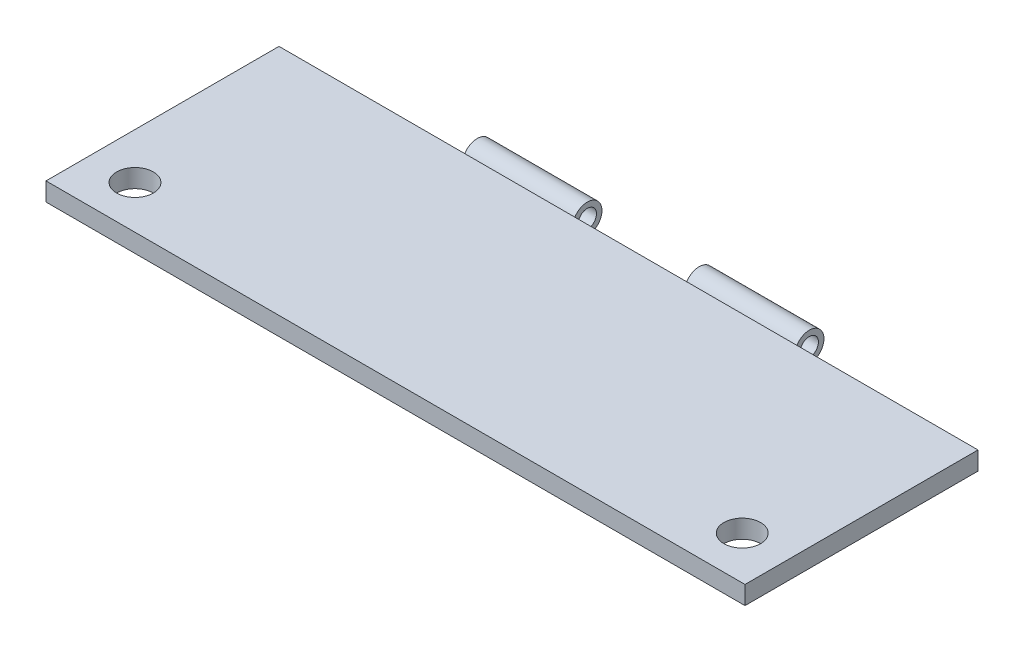
SolidWorks part; units mm, degrees
ref_plane "Alzado" through (0, 0, 0) normal (0, 0, 1) x (1, 0, 0)
ref_plane "Planta" through (0, 0, 0) normal (0, 1, 0) x (1, 0, 0)
ref_plane "Vista lateral" through (0, 0, 0) normal (1, 0, 0) x (0, 0, -1)
sketch "Croquis1" plane through (0, 0, 0) normal (0, 1, 0) x (1, 0, 0)
  line L1 (-38.1, -12.7) -> (38.1, -12.7)
  line L2 (-38.1, -12.7) -> (-38.1, 12.7)
  line L3 (-38.1, 12.7) -> (38.1, 12.7)
  line L4 (38.1, -12.7) -> (38.1, 12.7)
  line L5 (-38.1, -12.7) -> (38.1, 12.7) construction
  line L6 (-38.1, 12.7) -> (38.1, -12.7) construction
  point P0 (0, 0)
  dimension "D1" = 76.2
  dimension "D2" = 25.4
extrude "Saliente-Extruir1" add sketch "Croquis1" along normal blind 2
sketch "Croquis2" plane through (-38.1, 0, 0) normal (-1, 0, 0) x (0, 0, 1)
  circle A0 centre (-14.3062, 0.901) radius 1.6
extrude "Saliente-Extruir2" add sketch "Croquis2" against normal up to surface (76.2 mm away) separate body up to face at (38.1, 1, 0)
sketch "Croquis3" plane through (0, 2, 0) normal (0, 1, 0) x (1, 0, 0)
  line L0 (-38.1, 0) -> (-33.1, 0)
  line L1 (-38.1, 12.7) -> (-38.1, -12.7) construction
  line L2 (-33.1, 0) -> (-33.1, -8)
  line L3 (38.1, 0) -> (33.1, 0)
  line L4 (38.1, -12.7) -> (38.1, 12.7) construction
  line L5 (33.1, 0) -> (33.1, -8)
  circle A0 centre (-33.1, -8) radius 2
  circle A1 centre (33.1, -8) radius 2
extrude "Cortar-Extruir1" cut sketch "Croquis3" against normal blind 2
sketch "Croquis4" plane through (-38.1, 0, 0) normal (-1, 0, 0) x (0, 0, 1)
  circle A0 centre (-14.3062, 0.901) radius 1
extrude "Cortar-Extruir2" cut sketch "Croquis4" against normal up to surface (76.2 mm away) up to face at (38.1, 0.901, -12.7062)
sketch "Croquis5" plane through (0, 2, 0) normal (0, 1, 0) x (1, 0, 0)
  line L0 (-38.1, 14.3062) -> (-18.1, 14.3062)
  line L1 (-38.1, 15.9062) -> (-38.1, 12.7062) construction
  line L2 (38.1, 14.3062) -> (18.1, 14.3062)
  line L3 (38.1, 12.7062) -> (38.1, 15.9062) construction
  line L4 (-18.1, 14.3062) -> (-6.1, 14.3062)
  line L5 (18.1, 14.3062) -> (6.1, 14.3062)
  line L7 (38.1, 12.7) -> (-38.1, 12.7) construction
  line L8 (-38.1, 15.9124) -> (-18.1, 15.9124)
  line L9 (-38.1, 15.9124) -> (-38.1, 12.7)
  line L10 (-38.1, 12.7) -> (-18.1, 12.7)
  line L11 (-18.1, 15.9124) -> (-18.1, 12.7)
  line L12 (-38.1, 15.9124) -> (-18.1, 12.7) construction
  line L14 (-38.1, 12.7) -> (-18.1, 15.9124) construction
  line L17 (18.1, 12.7062) -> (38.1, 12.7062)
  line L18 (18.1, 12.7062) -> (18.1, 15.9062)
  line L19 (18.1, 15.9062) -> (38.1, 15.9062)
  line L20 (38.1, 12.7062) -> (38.1, 15.9062)
  line L21 (18.1, 12.7062) -> (38.1, 15.9062) construction
  line L22 (18.1, 15.9062) -> (38.1, 12.7062) construction
  line L23 (-6.1, 12.7062) -> (6.1, 12.7062)
  line L24 (-6.1, 12.7062) -> (-6.1, 15.9062)
  line L25 (-6.1, 15.9062) -> (6.1, 15.9062)
  line L26 (6.1, 12.7062) -> (6.1, 15.9062)
  line L27 (-6.1, 12.7062) -> (6.1, 15.9062) construction
  line L28 (-6.1, 15.9062) -> (6.1, 12.7062) construction
  point P8 (-12.1, 14.3062)
  point P11 (-28.1, 14.3062)
  point P17 (12.1, 14.3062)
  point P19 (28.1, 14.3062)
  point P20 (28.1, 14.3062)
  point P25 (0, 14.3062)
  dimension "D1" = 20
  dimension "D2" = 12
  dimension "D3" = 12
  dimension "D4" = 20
extrude "Cortar-Extruir5" cut sketch "Croquis5" against normal up to surface (2 mm away) and the other way up to surface contours L11 L10 L9 L8 | L26 L25 L24 L23 | L20 L19 L18 L17 other way up to face at (38.1, 0.901, -12.7062)
